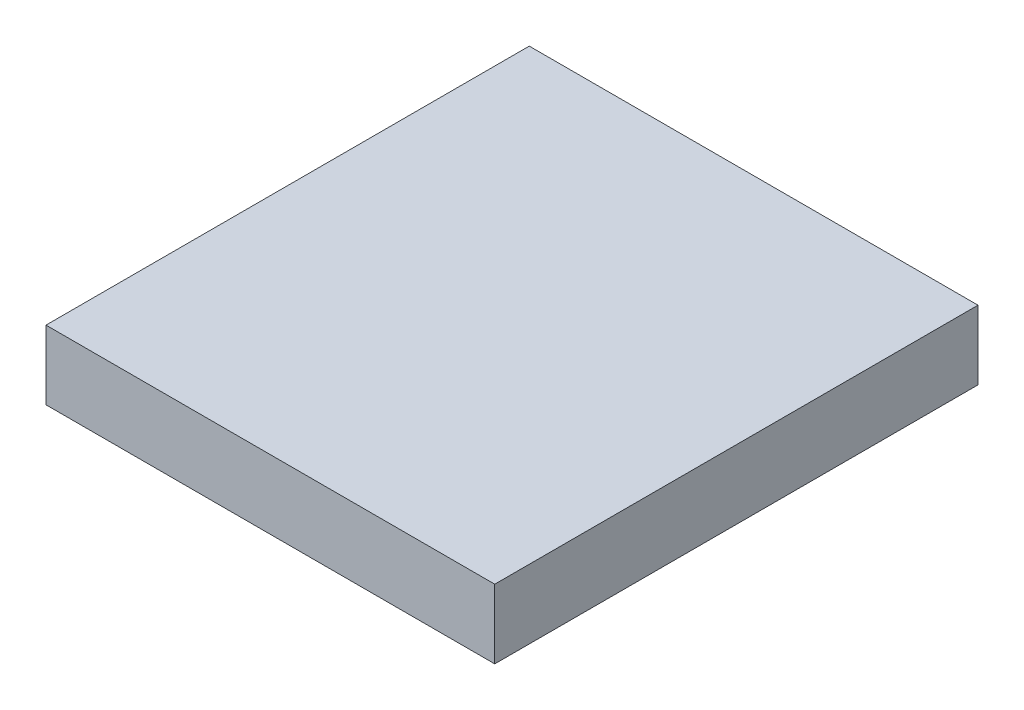
SolidWorks part; units mm, degrees
ref_plane "Front Plane" through (0, 0, 0) normal (0, 0, 1) x (1, 0, 0)
ref_plane "Top Plane" through (0, 0, 0) normal (0, 1, 0) x (1, 0, 0)
ref_plane "Right Plane" through (0, 0, 0) normal (1, 0, 0) x (0, 0, -1)
sketch "Sketch1" plane through (0, 0, 0) normal (0, 1, 0) x (1, 0, 0)
  line L1 (0, 0) -> (6.5, 0)
  line L2 (0, 0) -> (0, -7)
  line L3 (0, -7) -> (6.5, -7)
  line L4 (6.5, 0) -> (6.5, -7)
  dimension "D1" = 6.5
  dimension "D2" = 7
extrude "Boss-Extrude1" add sketch "Sketch1" along normal blind 1
